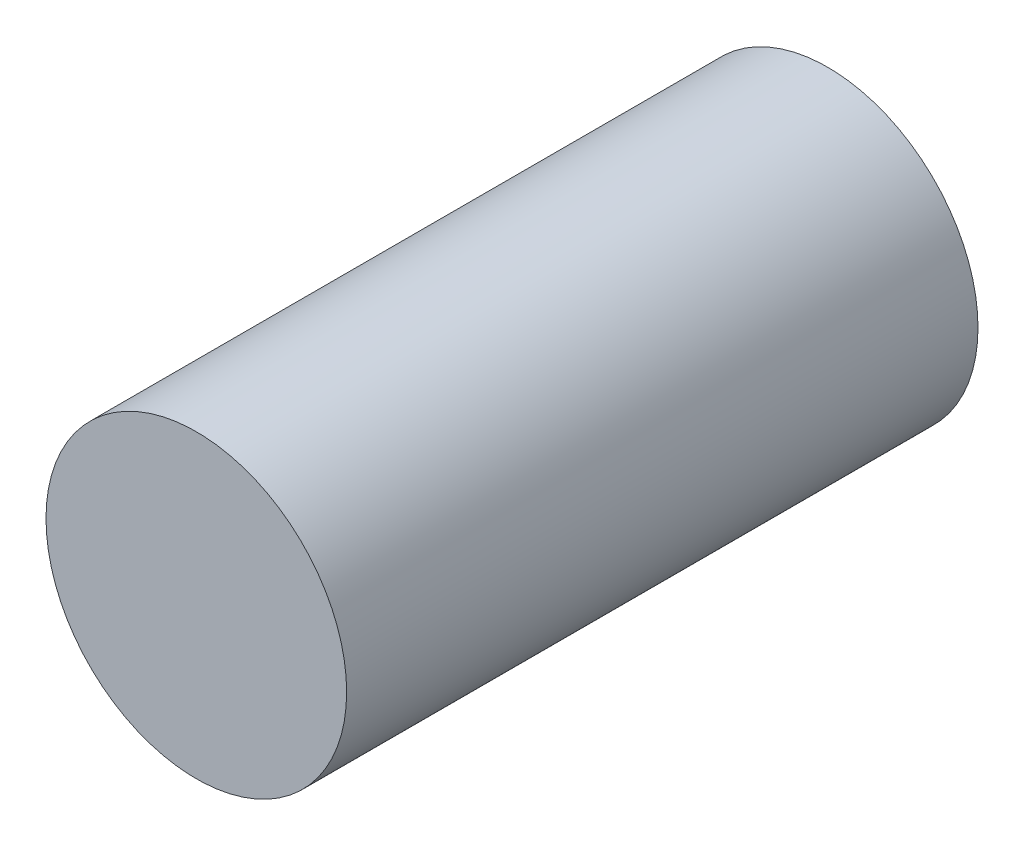
SolidWorks part; units mm, degrees
ref_plane "Alzado" through (0, 0, 0) normal (0, 0, 1) x (1, 0, 0)
ref_plane "Planta" through (0, 0, 0) normal (0, 1, 0) x (1, 0, 0)
ref_plane "Vista lateral" through (0, 0, 0) normal (1, 0, 0) x (0, 0, -1)
sketch "Croquis1" plane through (0, 0, 0) normal (0, 0, 1) x (1, 0, 0)
  circle A0 centre (0, 0) radius 7.5
  point P4 (0, 0)
  dimension "D1" = 15
extrude "Saliente-Extruir1" add sketch "Croquis1" along normal blind 31.5
